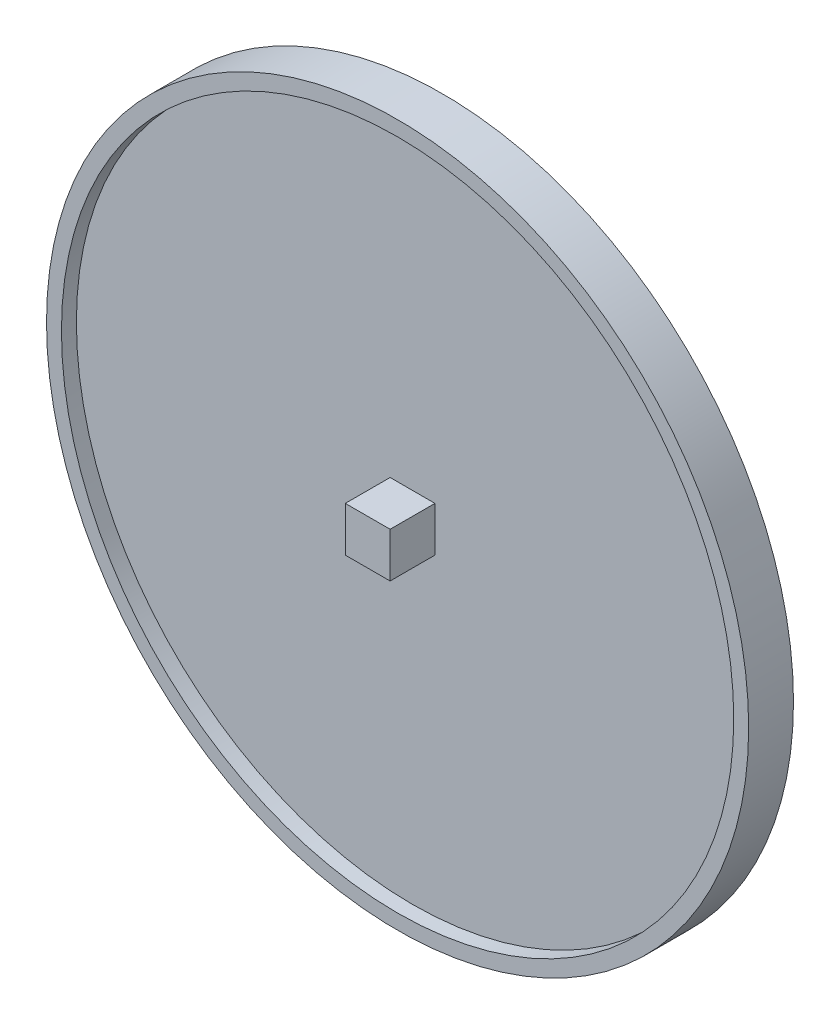
SolidWorks part; units mm, degrees
ref_plane "Piano frontale" through (0, 0, 0) normal (0, 0, 1) x (1, 0, 0)
ref_plane "Piano superiore" through (0, 0, 0) normal (0, 1, 0) x (1, 0, 0)
ref_plane "Piano destro" through (0, 0, 0) normal (1, 0, 0) x (0, 0, -1)
sketch "Schizzo1" plane through (0, 0, 0) normal (0, 0, 1) x (1, 0, 0)
  circle A0 centre (0, 0) radius 235
  dimension "D1" = 470
extrude "Estrusione-Estrusione1" add sketch "Schizzo1" along normal blind 20
sketch "Schizzo2" plane through (0, 0, 20) normal (0, 0, 1) x (1, 0, 0)
  circle A0 centre (0, 0) radius 235
  circle A1 centre (0, 0) radius 225
  circle A2 centre (0, 0) radius 235 construction
  dimension "D1" = 450
extrude "Estrusione-Estrusione2" add sketch "Schizzo2" along normal blind 10
sketch "Schizzo3" plane through (0, 0, 20) normal (0, 0, 1) x (1, 0, 0)
  line L1 (15, -15) -> (-15, -15)
  line L2 (15, -15) -> (15, 15)
  line L3 (15, 15) -> (-15, 15)
  line L4 (-15, -15) -> (-15, 15)
  line L5 (15, -15) -> (-15, 15) construction
  line L6 (15, 15) -> (-15, -15) construction
  point P0 (0, 0)
  dimension "D1" = 30
  dimension "D2" = 30
extrude "Estrusione-Estrusione3" add sketch "Schizzo3" along normal blind 30
